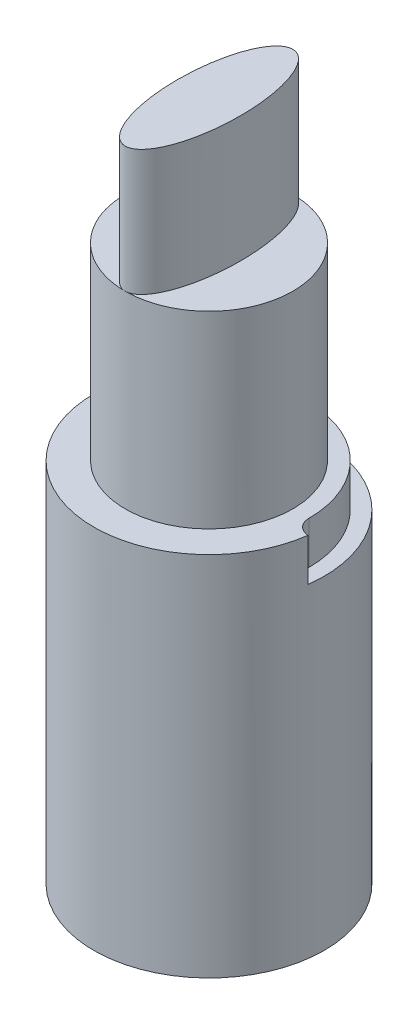
SolidWorks part; units mm, degrees
material "Brass"
ref_plane "Front Plane" through (0, 0, 0) normal (0, 0, 1) x (1, 0, 0)
ref_plane "Top Plane" through (0, 0, 0) normal (0, 1, 0) x (1, 0, 0)
ref_plane "Right Plane" through (0, 0, 0) normal (1, 0, 0) x (0, 0, -1)
ref_plane "Plane1" through (0, 0, 24.4095) normal (0, 0, 1) x (1, 0, 0)
sketch "Sketch1" plane through (-15.0343, 949.0981, 12.4095) normal (0, 1, 0) x (0, 0, 1)
  line L0 (5, 0) -> (35, 0) construction
  ellipse E0 centre (20, 0) end of major axis (12, 0) minor radius 3
  point P1 (28, 0)
  point P7 (12, 0)
  dimension "D1" = 8
  dimension "D2" = 3
extrude "Boss-Extrude1" add sketch "Sketch1" along a picked direction on the side against the normal blind 12
sketch "Sketch3" plane through (0, 937.0981, 0) normal (0, -1, 0) x (1, 0, 0)
  line L0 (-15.0343, 17.4095) -> (-15.0343, 47.4095) construction
  circle A0 centre (-15.0343, 32.4095) radius 8
  ellipse E1 centre (-15.0343, 32.4095) end of major axis (-15.0343, 24.4095) minor radius 3 construction
  point P4 (-15.0343, 40.4095)
extrude "Boss-Extrude2" add sketch "Sketch3" along normal up to vertex (18 mm away)
sketch "Sketch13" plane through (0, 919.0981, 0) normal (0, -1, 0) x (1, 0, 0)
  line L0 (-15.0343, 17.4095) -> (-15.0343, 47.4095) construction
  circle A0 centre (-15.0343, 32.4095) radius 11
  dimension "D1" = 22
extrude "Boss-Extrude3" add sketch "Sketch13" along normal blind 35 contours A0
sketch "Sketch14" [suppressed] plane through (0, 884.0981, 0) normal (0, -1, 0) x (1, 0, 0)
  line L0 (-2.9448, 17.4095) -> (-2.9448, 47.4095) construction
  line L3 (5.0552, 32.4095) -> (5.0552, 33.4095) construction
  line L7 (-3.9448, 31.2915) -> (-3.9448, 28.5366)
  line L8 (-3.9448, 24.4095) -> (-2.9448, 24.4095) construction
  line L9 (-1.8268, 33.4095) -> (-1.8268, 32.4095) construction
  line L10 (-1.8268, 32.4095) -> (5.0552, 32.4095) construction
  line L11 (-1.8268, 32.4095) -> (-2.9448, 32.4095) construction
  line L12 (5.0552, 32.4095) -> (5.0552, 31.4095) construction
  line L13 (-2.9448, 24.4095) -> (-1.9448, 24.4095) construction
  line L17 (-2.9448, 32.4095) -> (-6.9448, 32.4095) construction
  line L19 (2.1796, 35.2777) -> (-1.8268, 33.4095)
  line L20 (-2.9448, 32.4095) -> (-2.9448, 31.2915) construction
  line L21 (-2.9448, 31.2915) -> (-3.9448, 31.2915) construction
  line L23 (-6.9448, 32.4095) -> (-11.007, 32.4095) construction
  arc A0 (-2.9448, 24.4095) -> (5.0552, 32.4095) centre (-2.9448, 32.4095) ccw construction
  arc A1 (-1.9448, 24.4095) -> (5.0552, 31.4095) centre (-2.9448, 32.4095) ccw
  arc A2 (5.0552, 31.4095) -> (5.0552, 33.4095) centre (-2.9448, 32.4095) ccw
  arc A3 (-3.9448, 24.4095) -> (-1.9448, 24.4095) centre (-2.9448, 32.4095) ccw
  arc A4 (5.0552, 33.4095) -> (4.9943, 33.8134) centre (-2.9448, 32.4095) ccw
  circle A5 centre (-2.9448, 32.4095) radius 11 construction
  arc A6 (-1.8268, 33.4095) -> (-3.9448, 31.2915) centre (-2.9448, 32.4095) ccw
  arc A8 (4.9943, 33.8134) -> (2.1796, 35.2777) centre (3.0249, 33.4651) ccw
  arc A9 (-3.9448, 24.4095) -> (-11.007, 32.4095) centre (-2.9448, 32.4095) cw
  arc A10 (-3.9448, 28.5366) -> (-6.9448, 32.4095) centre (-2.9448, 32.4095) cw
  arc A11 (-6.9448, 32.4095) -> (-11.007, 32.4095) centre (-8.9759, 32.4095) ccw
  circle A12 centre (-2.9448, 32.4095) radius 8.0623 construction
  dimension "D1" = 3
  dimension "D3" = 3
  dimension "D5" = 4
  dimension "D6" = 2
  dimension "D2" = 1
  dimension "D4" = 25
extrude "DEPRECIATED Cut-Extrude2" [suppressed] cut sketch "Sketch14" against normal offset from surface (986.0981 mm away) 3
sketch "Sketch16" [suppressed] plane through (0, 884.0981, 0) normal (0, -1, 0) x (1, 0, 0)
  line L0 (-2.9448, 17.4095) -> (-2.9448, 47.4095) construction
  line L3 (-2.9448, 32.4095) -> (-1.8268, 32.4095) construction
  line L4 (-1.8268, 32.4095) -> (-1.8268, 33.4095) construction
  line L5 (-1.8268, 36.2501) -> (-1.8268, 35.5131) construction
  line L8 (2.1796, 35.2777) -> (-1.8268, 33.4095) construction
  line L9 (-1.8268, 33.4095) -> (0.9282, 33.4095)
  line L10 (-1.8268, 35.5131) -> (-1.8268, 33.4095)
  arc A0 (0.9282, 33.4095) -> (-1.0956, 35.9564) centre (-2.9448, 32.4095) ccw
  arc A1 (-1.8268, 33.4095) -> (-3.9448, 31.2915) centre (-2.9448, 32.4095) ccw construction
  arc A2 (-1.8268, 33.4095) -> (-3.9448, 31.2915) centre (-2.9448, 32.4095) ccw construction
  arc A3 (-1.0956, 35.9564) -> (-1.8268, 35.5131) centre (-1.3268, 35.5131) ccw
  arc A4 (-1.0956, 35.9564) -> (-1.8268, 36.2501) centre (-2.9448, 32.4095) ccw construction
  dimension "D1" = 8
extrude "DEPRECIATED Cut-Extrude4" [suppressed] cut sketch "Sketch16" against normal offset from surface (29 mm away) 3
sketch "Sketch18" plane through (0, 884.0981, 0) normal (0, -1, 0) x (1, 0, 0)
  circle A0 centre (-15.0343, 32.4095) radius 8
  dimension "D1" = 16
extrude "Cut-Extrude5" cut sketch "Sketch18" against normal offset from surface (29 mm away) 6 up to face at (-15.0343, 919.0981, 24.4095)
sketch "Sketch19" plane through (0, 913.0981, 0) normal (0, -1, 0) x (1, 0, 0)
  line L0 (-16.0343, 31.2915) -> (-16.0343, 25.4095)
  line L2 (-13.9162, 33.4095) -> (-13.9162, 32.4095) construction
  line L4 (-13.9162, 33.4095) -> (-8.0343, 33.4095)
  line L5 (-7.0343, 32.4095) -> (-7.0343, 41.3314) construction
  line L7 (-15.0343, 32.4095) -> (-7.0343, 32.4095) construction
  line L8 (-16.0949, 33.4702) -> (-9.3774, 26.7527) construction
  arc A1 (-7.0343, 32.4095) -> (-15.0343, 24.4095) centre (-15.0343, 32.4095) cw
  circle A3 centre (-15.0343, 32.4095) radius 8 construction
  arc A5 (-13.9162, 33.4095) -> (-16.0343, 31.2915) centre (-15.0343, 32.4095) ccw
  arc A7 (-16.0343, 31.2915) -> (-13.9162, 33.4095) centre (-15.0343, 32.4095) ccw construction
  arc A8 (-7.0343, 32.4095) -> (-8.0343, 33.4095) centre (-8.0343, 32.4095) ccw
  arc A10 (-15.0343, 24.4095) -> (-16.0343, 25.4095) centre (-15.0343, 25.4095) cw
  dimension "D1" = 3
  dimension "D3" = 45
  dimension "D2" = 1
extrude "Cut-Extrude6" cut sketch "Sketch19" against normal blind 4
sketch "Sketch20" plane through (0, 919.0981, 0) normal (0, 1, 0) x (1, 0, 0)
  arc A0 (-15.0343, -21.4095) -> (-4.0343, -32.4095) centre (-15.0343, -32.4095) cw construction
  circle A1 centre (-15.0343, -32.4095) radius 11 construction
  arc A2 (-5.4948, -32.4095) -> (-2.5738, -32.4095) centre (-4.0343, -32.4095) ccw
  arc A3 (-15.0343, -19.949) -> (-15.0343, -22.87) centre (-15.0343, -21.4095) ccw
  arc A4 (-15.0343, -22.87) -> (-5.4948, -32.4095) centre (-15.0343, -32.4095) cw
  arc A5 (-15.0343, -19.949) -> (-2.5738, -32.4095) centre (-15.0343, -32.4095) cw
  dimension "D1" = 2.921
extrude "Cut-Extrude7" cut sketch "Sketch20" against normal blind 4.064
ref_plane "Plane2" through (0, 0, 21.4095) normal (0, 0, -1) x (-1, 0, 0)
sketch "Sketch21" plane through (0, 0, 21.4095) normal (0, 0, 1) x (1, 0, 0)
  line L0 (-4.0343, 886.5981) -> (-26.0343, 886.5981) construction
  line L1 (-4.0343, 884.0981) -> (-4.0343, 915.0341) construction
  line L3 (-26.0343, 919.0981) -> (-26.0343, 884.0981) construction
  line L4 (-15.0343, 885.1376) -> (-15.0343, 884.0981) construction
  line L5 (-26.0343, 884.0981) -> (-4.0343, 884.0981) construction
  line L6 (-15.0343, 886.5981) -> (-15.0343, 890.0981) construction
  circle A0 centre (-15.0343, 886.5981) radius 1.4605
  circle A1 centre (-15.0343, 890.0981) radius 1.4605 construction
  dimension "D1" = 2.921
  dimension "D3" = 3.5
  dimension "D2" = 1.0395
extrude "Cut-Extrude8" cut sketch "Sketch21" along normal up to surface (3.1344 mm away)
pattern_linear "LPattern1" count 7 spacing 3.5 along (0, 1, 0) of "Cut-Extrude8"
